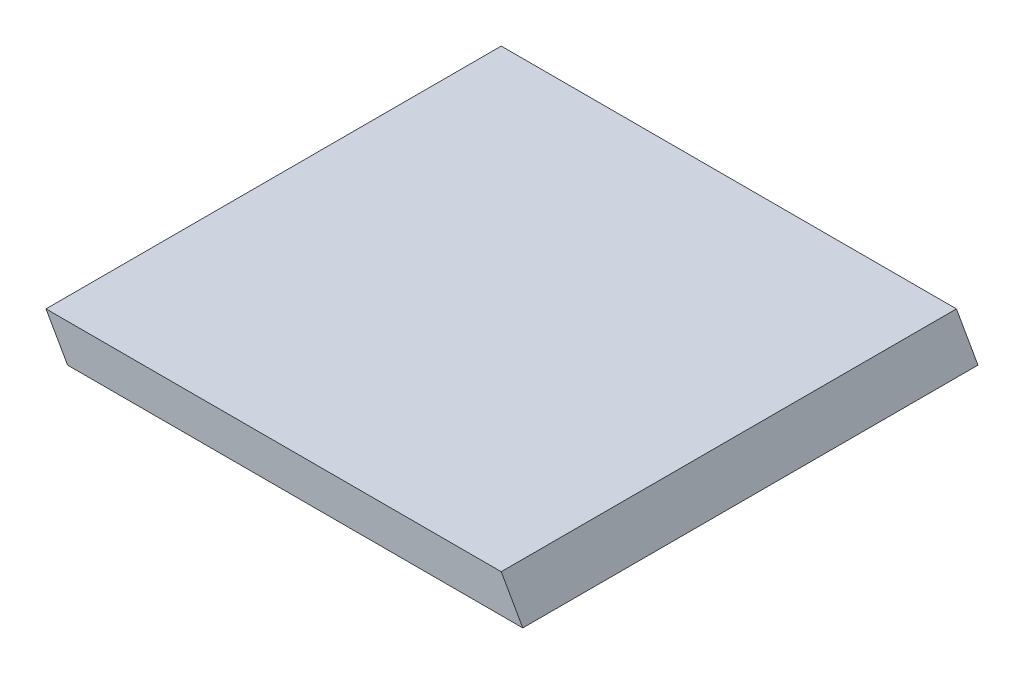
SolidWorks part; units mm, degrees
material "Glass"
ref_plane "Front Plane" through (0, 0, 0) normal (0, 0, 1) x (1, 0, 0)
ref_plane "Top Plane" through (0, 0, 0) normal (0, 1, 0) x (1, 0, 0)
ref_plane "Right Plane" through (0, 0, 0) normal (1, 0, 0) x (0, 0, -1)
sketch "Sketch1" plane through (0, 0, 0) normal (0, 1, 0) x (1, 0, 0)
  line L1 (-3.81, -3.81) -> (3.81, -3.81)
  line L2 (-3.81, -3.81) -> (-3.81, 3.81)
  line L3 (-3.81, 3.81) -> (3.81, 3.81)
  line L4 (3.81, -3.81) -> (3.81, 3.81)
  line L5 (-3.81, -3.81) -> (3.81, 3.81) construction
  line L6 (-3.81, 3.81) -> (3.81, -3.81) construction
  point P0 (0, 0)
  dimension "D1" = 7.62
  dimension "D2" = 7.62
ref_plane "Plane1" through (0, 0, 0) normal (0, 1, 0) x (1, 0, 0)
ref_plane "Plane2" through (0, 0.635, 0) normal (0, 1, 0) x (1, 0, 0)
sketch "Sketch2" plane through (0, 0.635, 0) normal (0, 1, 0) x (1, 0, 0)
  line L1 (-4.171, 3.81) -> (3.449, 3.81)
  line L2 (-4.171, 3.81) -> (-4.171, -3.81)
  line L3 (-4.171, -3.81) -> (3.449, -3.81)
  line L4 (3.449, 3.81) -> (3.449, -3.81)
  line L5 (-4.171, 3.81) -> (3.449, -3.81) construction
  line L6 (-4.171, -3.81) -> (3.449, 3.81) construction
  line L7 (-3.81, -3.81) -> (3.81, -3.81) construction
  dimension "D1" = 7.62
  dimension "D2" = 7.62
loft "Loft1" add profiles "Sketch2", "Sketch1"
